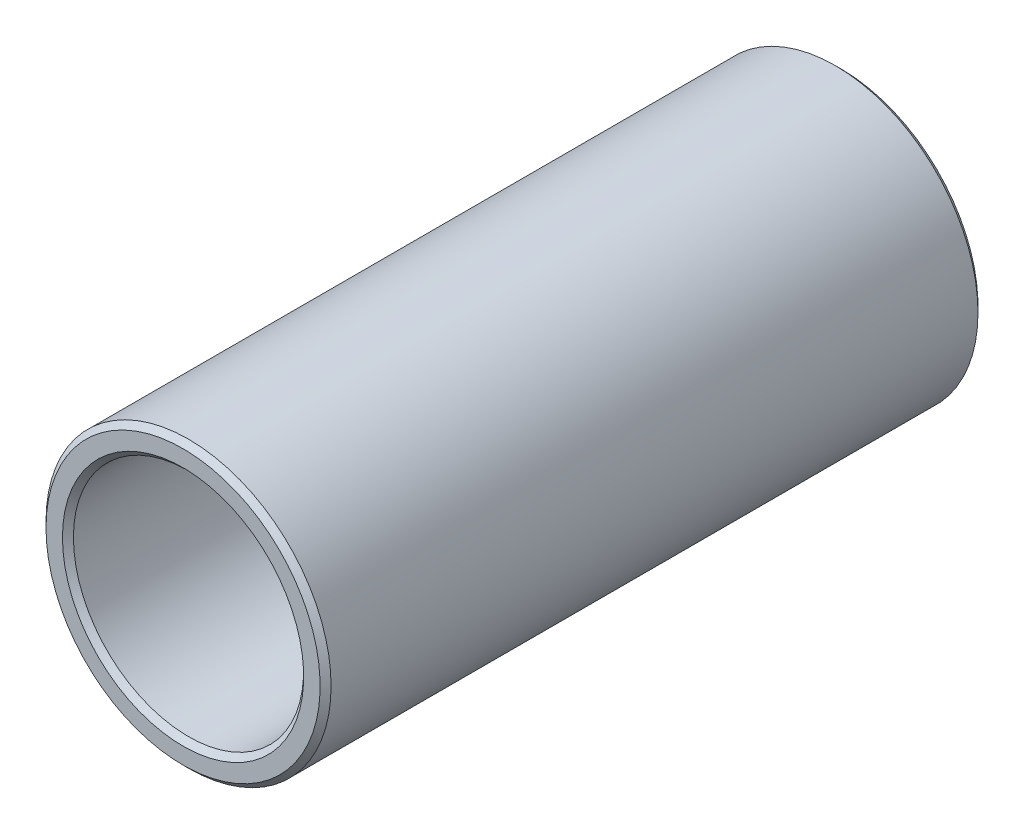
SolidWorks part; units mm, degrees
ref_plane "Спереди" through (0, 0, 0) normal (0, 0, 1) x (1, 0, 0)
ref_plane "Сверху" through (0, 0, 0) normal (0, 1, 0) x (1, 0, 0)
ref_plane "Справа" through (0, 0, 0) normal (1, 0, 0) x (0, 0, -1)
ref_plane "Плоскость4" through (0, 0, 0) normal (0, -1, 0) x (1, 0, 0)
sketch "Эскиз1" plane through (0, 0, 0) normal (0, -1, 0) x (1, 0, 0)
  line L0 (5.053, 0.947) -> (6, 0)
  line L1 (6, 0) -> (12.5, 0)
  line L2 (12.5, 0) -> (13, 0.5)
  line L3 (13, 0.5) -> (13, 59.5)
  line L4 (13, 59.5) -> (12.5, 60)
  line L5 (12.5, 60) -> (11, 60)
  line L6 (11, 60) -> (10.5, 59.5)
  line L7 (10.5, 59.5) -> (10.5, 13)
  line L8 (10.5, 13) -> (5.053, 12.053)
  line L9 (5.053, 12.053) -> (5.053, 0.947)
  line L10 (0, 60.005) -> (0, -0.005) construction
revolve "Повернуть1" add sketch "Эскиз1" angle 360 about L10
